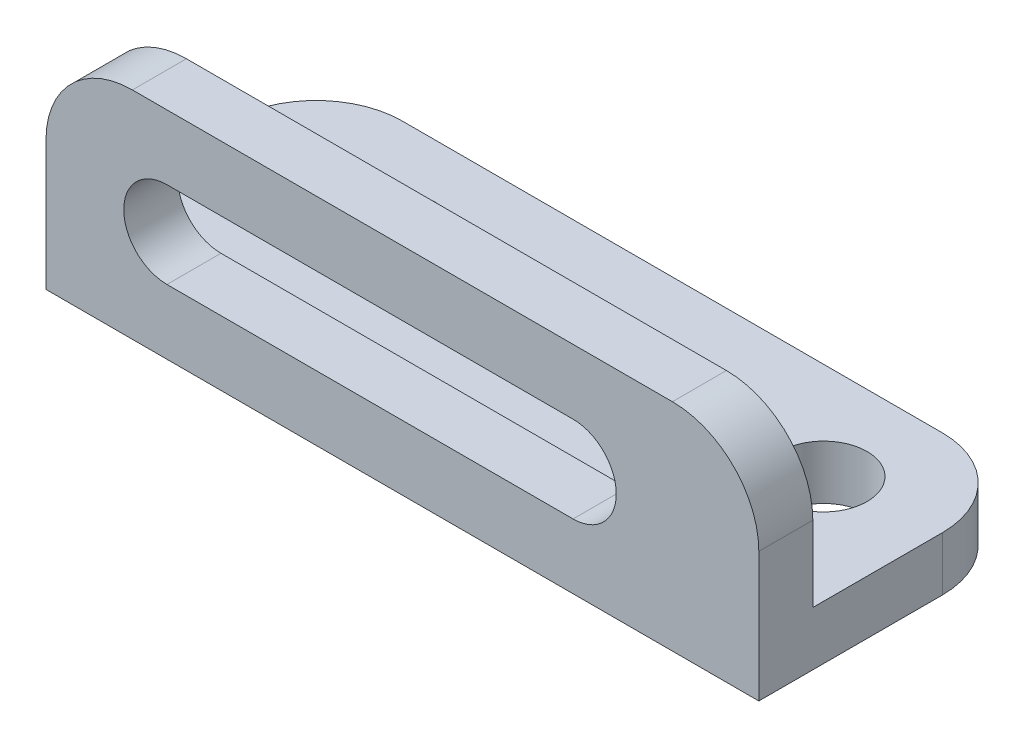
SolidWorks part; units mm, degrees
ref_plane "Front Plane" through (0, 0, 0) normal (0, 0, 1) x (1, 0, 0)
ref_plane "Top Plane" through (0, 0, 0) normal (0, 1, 0) x (1, 0, 0)
ref_plane "Right Plane" through (0, 0, 0) normal (1, 0, 0) x (0, 0, -1)
ref_plane "Plane1" through (0, 6.35, 0) normal (0, 1, 0) x (1, 0, 0)
sketch "Sketch1" plane through (0, 6.35, 0) normal (0, 1, 0) x (1, 0, 0)
  line L0 (-20.955, 0) -> (20.955, 0)
  line L1 (20.955, 0) -> (20.955, 15.875)
  line L2 (20.955, 15.875) -> (-20.955, 15.875)
  line L3 (-20.955, 15.875) -> (-20.955, 0)
  dimension "D1" = 15.875
  dimension "D2" = 41.91
extrude "Boss-Extrude1" add sketch "Sketch1" against normal blind 12.7
sketch "Sketch2" plane through (20.955, 0, 0) normal (1, 0, 0) x (0, 0, -1)
  line L0 (3.175, -3.175) -> (15.875, -3.175)
  line L1 (15.875, -3.175) -> (15.875, 6.35)
  line L2 (15.875, 6.35) -> (3.175, 6.35)
  line L3 (3.175, 6.35) -> (3.175, -3.175)
extrude "Cut-Extrude1" cut sketch "Sketch2" against normal through all
sketch "Sketch3" plane through (0, 0, 0) normal (0, 0, 1) x (1, 0, 0)
  line L0 (-13.843, -2.54) -> (10.033, -2.54)
  line L1 (10.033, 2.54) -> (-13.843, 2.54)
  arc A0 (10.033, -2.54) -> (10.033, 2.54) centre (10.033, 0) ccw
  arc A1 (-13.843, 2.54) -> (-13.843, -2.54) centre (-13.843, 0) ccw
extrude "Cut-Extrude2" cut sketch "Sketch3" against normal through all
hole_wizard "Hole1" positions "Sketch5" profile "Sketch4" legacy
sketch "Sketch5" plane through (0, -6.35, 0) normal (0, -1, 0) x (-1, 0, 0)
  point P0 (10.795, 10.16)
  point P1 (-14.605, 10.16)
sketch "Sketch4" plane through (-10.795, -6.35, -10.16) normal (1, 0, 0) x (0, 0, -1)
  line L0 (0, 0) -> (0, 12.7)
  line L1 (0, 12.7) -> (2.5527, 12.7)
  line L2 (2.5527, 12.7) -> (2.5527, 0)
  line L3 (2.5527, 0) -> (0, 0)
  line L4 (0, 110) -> (0, -10) construction
  dimension "Diameter" = 5.1054
  dimension "Depth" = 12.7
fillet "Fillet1" radius 5.08 4 edges at (20.955, -4.7625, -15.875) (-20.955, -4.7625, -15.875) (20.955, 6.35, -1.5875) (-20.955, 6.35, -1.5875)
